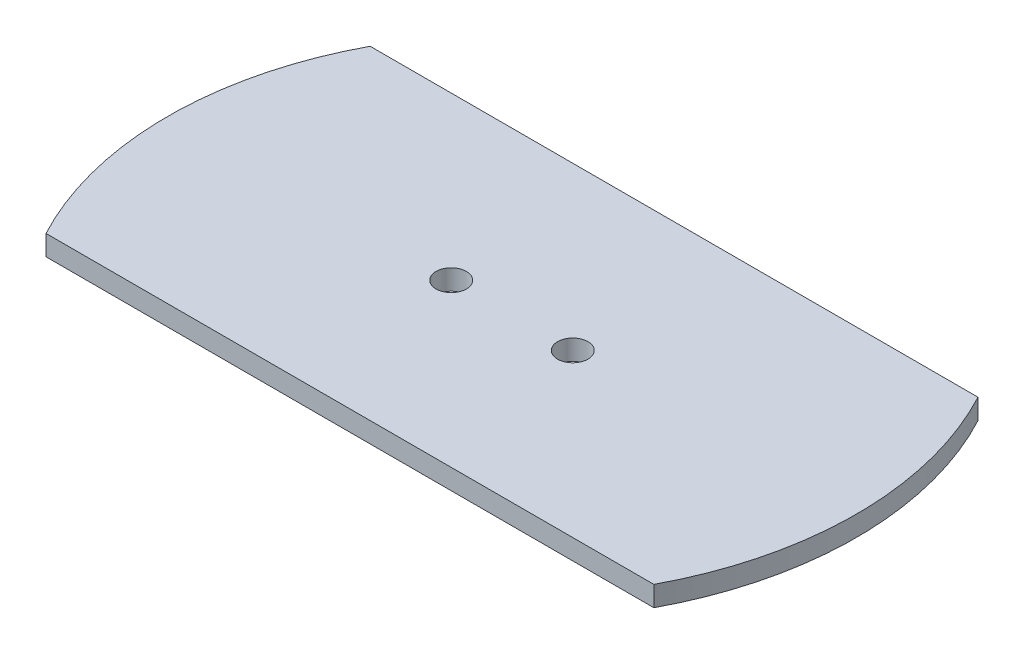
SolidWorks part; units mm, degrees
ref_plane "Front Plane" through (0, 0, 0) normal (0, 0, 1) x (1, 0, 0)
ref_plane "Top Plane" through (0, 0, 0) normal (0, 1, 0) x (1, 0, 0)
ref_plane "Right Plane" through (0, 0, 0) normal (1, 0, 0) x (0, 0, -1)
sketch "Sketch1" plane through (0, 0, 0) normal (0, 1, 0) x (1, 0, 0)
  line L0 (0, 0) -> (95.25, 0)
  line L1 (0, -50.8) -> (95.25, -50.8)
  line L2 (0, 0) -> (0, -50.8) construction
  arc A0 (0, 0) -> (0, -50.8) centre (47.625, -25.4) ccw
  arc A1 (95.25, 0) -> (95.25, -50.8) centre (47.625, -25.4) cw
  point P8 (-6.35, -25.4)
  point P9 (101.6, -25.4)
  dimension "D1" = 53.975
  dimension "D2" = 107.95
  dimension "D3" = 50.8
extrude "Boss-Extrude1" add sketch "Sketch1" along normal blind 3.175
sketch "Sketch2" plane through (0, 3.175, 0) normal (0, 1, 0) x (1, 0, 0)
  line L0 (47.625, 0) -> (47.625, -50.8) construction
  line L1 (95.25, 0) -> (0, 0) construction
  line L2 (0, -50.8) -> (95.25, -50.8) construction
  line L3 (47.625, -25.4) -> (57.15, -25.4) construction
  line L4 (47.625, -25.4) -> (38.1, -25.4) construction
  circle A0 centre (38.1, -25.4) radius 2.3812
  circle A1 centre (57.15, -25.4) radius 2.3812
  dimension "D2" = 4.7625
  dimension "D1" = 19.05
extrude "Cut-Extrude1" cut sketch "Sketch2" against normal blind 3.175
